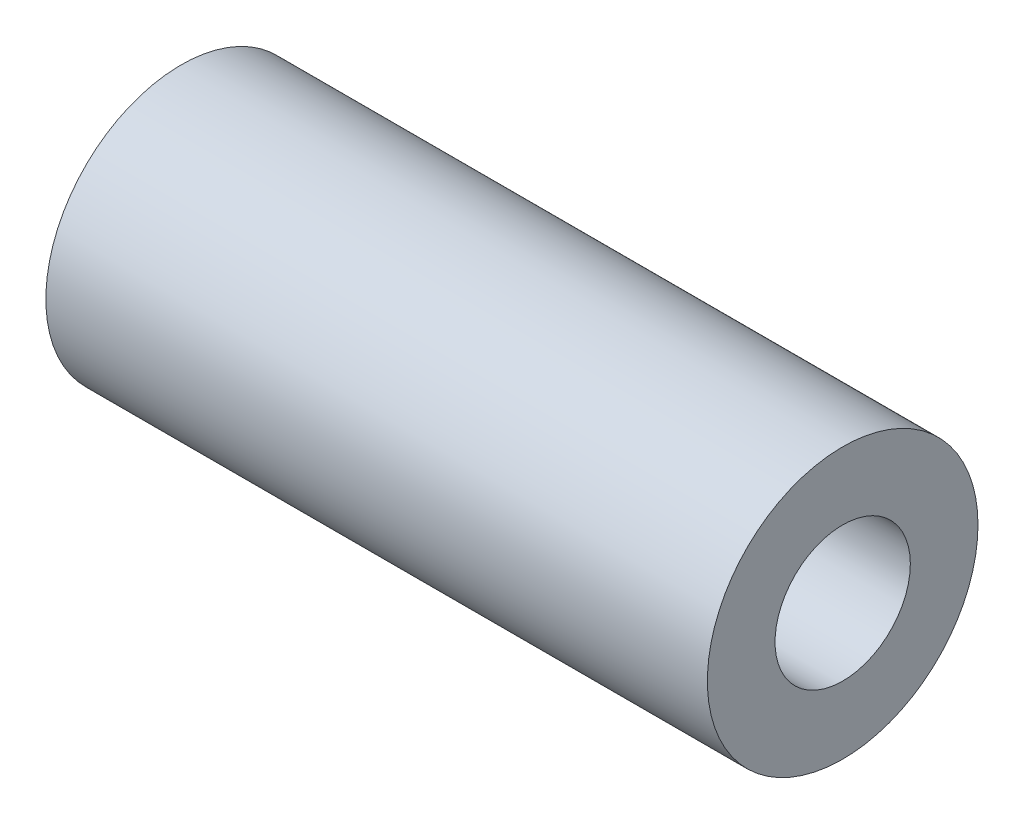
SolidWorks part; units mm, degrees
material "6061-T6 (SS)"
ref_plane "Alzado" through (0, 0, 0) normal (0, 0, 1) x (1, 0, 0)
ref_plane "Planta" through (0, 0, 0) normal (0, 1, 0) x (1, 0, 0)
ref_plane "Vista lateral" through (0, 0, 0) normal (1, 0, 0) x (0, 0, -1)
sketch "Croquis1" plane through (0, 0, 0) normal (1, 0, 0) x (0, 0, -1)
  circle A0 centre (0, 0) radius 4.5
  dimension "D1" = 9
extrude "Saliente-Extruir1" add sketch "Croquis1" along normal mid plane 22
hole_wizard "Taladro de margen para M41" positions "Croquis2" profile "Croquis3" hole size "M4" standard "Ansi Metric" end condition up to next
sketch "Croquis2" plane through (11, 0, 0) normal (1, 0, 0) x (0, 0, -1)
  point P0 (0, 0)
sketch "Croquis3" plane through (11, 0, 0) normal (0, 1, 0) x (0, 0, -1)
  line L0 (0, 0) -> (0, 22)
  line L1 (0, 22) -> (2.25, 22)
  line L2 (2.25, 22) -> (2.25, 0)
  line L5 (2.25, 0) -> (0, 0)
  line L11 (0, -6.35) -> (0, 107.95) construction
  dimension "Diámetro de taladro hasta el siguiente" = 4.5
  dimension "Profundidad de taladro hasta el siguiente" = 22
